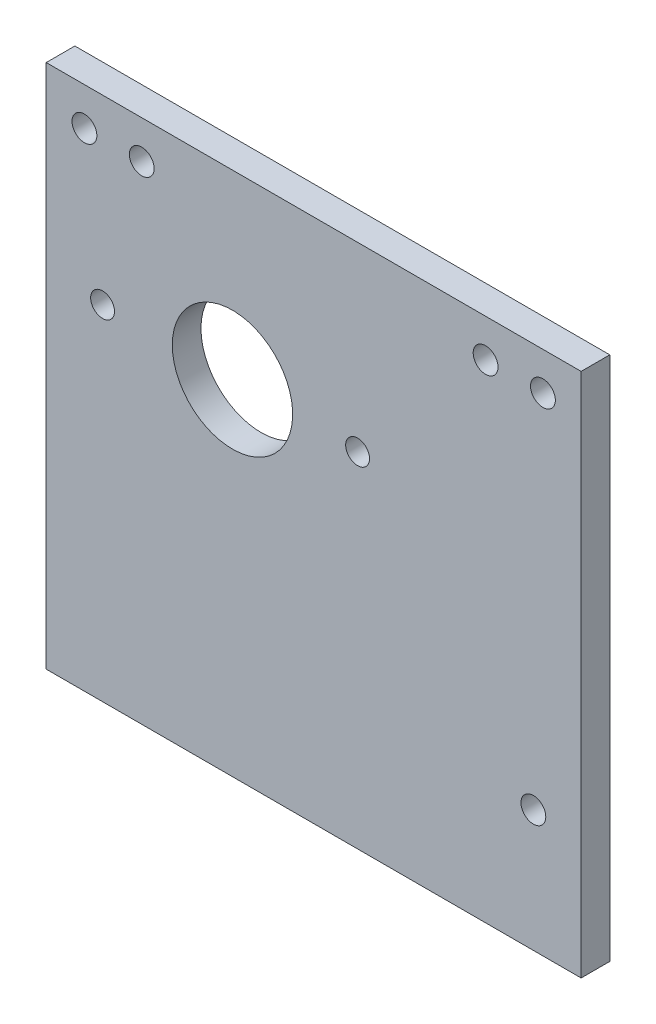
SolidWorks part; units mm, degrees
ref_plane "Alzado" through (0, 0, 0) normal (0, 0, 1) x (1, 0, 0)
ref_plane "Planta" through (0, 0, 0) normal (0, 1, 0) x (1, 0, 0)
ref_plane "Vista lateral" through (0, 0, 0) normal (1, 0, 0) x (0, 0, -1)
sketch "Croquis1" plane through (0, 0, 0) normal (0, 0, 1) x (1, 0, 0)
  line L5 (-26.5, -27.5) -> (29.5, -27.5)
  line L6 (-26.5, -27.5) -> (-26.5, 27.5)
  line L7 (-26.5, 27.5) -> (29.5, 27.5)
  line L8 (29.5, -27.5) -> (29.5, 27.5)
  line L9 (-26.5, -27.5) -> (29.5, 27.5) construction
  line L10 (-26.5, 27.5) -> (29.5, -27.5) construction
  point P0 (1.5, 0)
extrude "Saliente-Extruir1" add sketch "Croquis1" along normal blind 3
sketch "Croquis2" plane through (0, 0, 3) normal (0, 0, 1) x (1, 0, 0)
  line L1 (24.5, -14.75) -> (24.5, -27.5)
  line L2 (-26.5, -27.5) -> (29.5, -27.5) construction
  line L3 (24.5, -27.5) -> (29.5, -27.5)
  line L4 (25.5, 23.5288) -> (29.5, 23.5288)
  line L5 (25.5, 23.5288) -> (19.5, 23.5288)
  line L6 (29.5, -27.5) -> (29.5, 27.5) construction
  line L7 (-16.5, 23.5288) -> (-22.5, 23.5288)
  line L8 (-26.5, 27.5) -> (-26.5, -27.5) construction
  circle A3 centre (25.5, 23.5288) radius 1.3
  circle A4 centre (24.5, -14.75) radius 1.3
  circle A5 centre (19.5, 23.5288) radius 1.3
  circle A6 centre (-16.5, 23.5288) radius 1.3
  circle A7 centre (-22.5, 23.5288) radius 1.3
  dimension "D1" = 4
extrude "Cortar-Extruir1" cut sketch "Croquis2" against normal blind 4
sketch "Croquis3" plane through (0, 0, 0) normal (0, 0, -1) x (-1, 0, 0)
  line L0 (7, 8.5) -> (26.5, 8.5)
  line L2 (26.5, 27.5) -> (26.5, -27.5) construction
  line L3 (20.6, 8.5) -> (7, 8.5)
  line L4 (7, 8.5) -> (-6.1, 8.5)
  circle A0 centre (7, 8.5) radius 6.3
  circle A2 centre (20.6, 8.5) radius 1.25
  circle A3 centre (-6.1, 8.5) radius 1.25
  dimension "D1" = 13.6
extrude "Cortar-Extruir2" cut sketch "Croquis3" against normal blind 4
